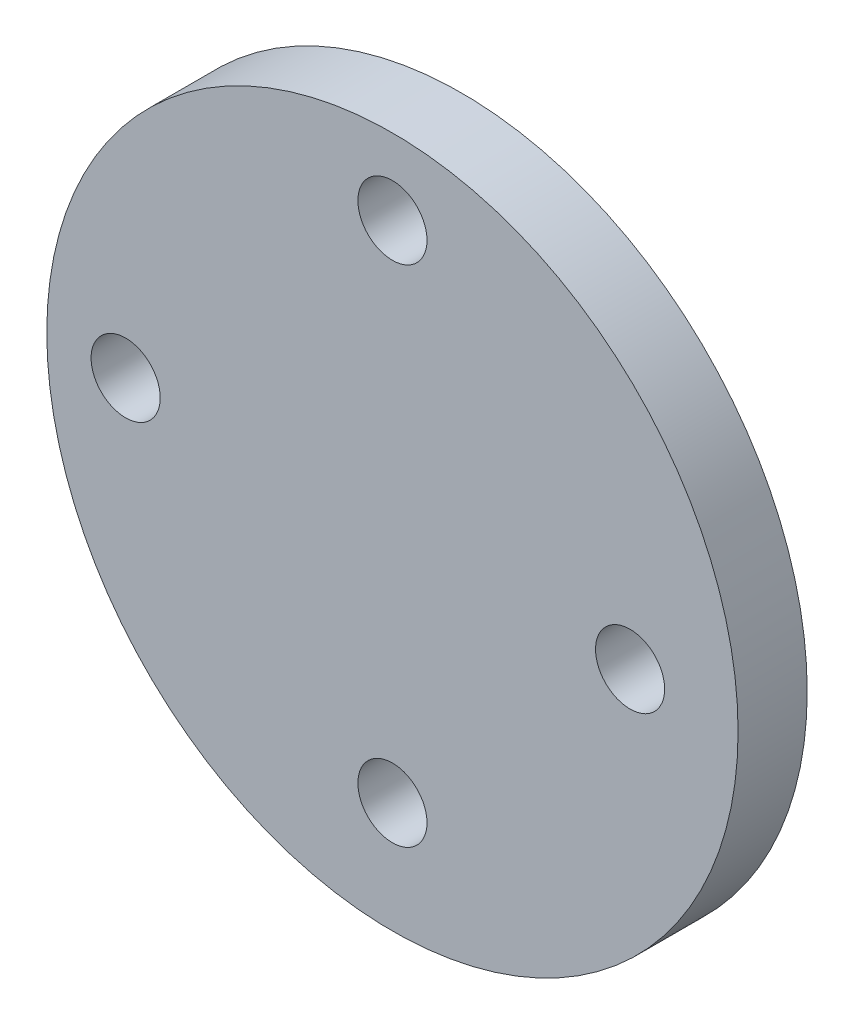
SolidWorks part; units mm, degrees
ref_plane "Front Plane" through (0, 0, 0) normal (0, 0, 1) x (1, 0, 0)
ref_plane "Top Plane" through (0, 0, 0) normal (0, 1, 0) x (1, 0, 0)
ref_plane "Right Plane" through (0, 0, 0) normal (1, 0, 0) x (0, 0, -1)
sketch "Sketch1" plane through (0, 0, 0) normal (0, 0, 1) x (1, 0, 0)
  circle A0 centre (0, 0) radius 50
  circle A1 centre (0, 39.0277) radius 5
  circle A2 centre (-38.5917, 0) radius 5
  circle A3 centre (0, -33.9403) radius 5
  circle A4 centre (34.3764, 0) radius 5
  dimension "D1" = 100
  dimension "D2" = 10
extrude "Boss-Extrude1" add sketch "Sketch1" along normal blind 10
